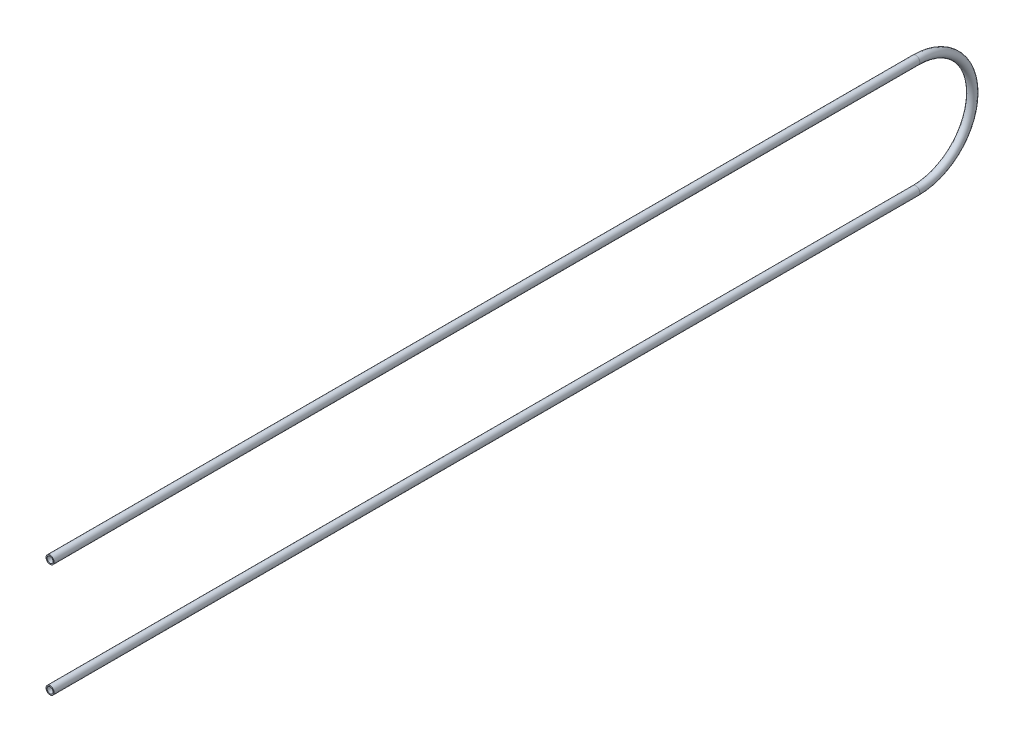
SolidWorks part; units mm, degrees
material "ASTM A312 TP316"
ref_plane "Front Plane" through (0, 0, 0) normal (0, 0, 1) x (1, 0, 0)
ref_plane "Top Plane" through (0, 0, 0) normal (0, 1, 0) x (1, 0, 0)
ref_plane "Right Plane" through (0, 0, 0) normal (1, 0, 0) x (0, 0, -1)
sketch "Sketch1" plane through (0, 0, 0) normal (1, 0, 0) x (0, 0, -1)
  line L0 (0, 0) -> (93.4526, 0) construction
  line L1 (0, 149.225) -> (2286, 149.225)
  line L2 (0, -149.225) -> (2286, -149.225)
  arc A0 (2286, -149.225) -> (2286, 149.225) centre (2286, 0) ccw
  dimension "D1" = 149.225
  dimension "D2" = 2286
sketch "Sketch2" plane through (0, 0, 0) normal (0, 0, 1) x (1, 0, 0)
  circle A0 centre (0, 149.225) radius 10.668
  circle A1 centre (0, 149.225) radius 7.8994
  dimension "D1" = 21.336
  dimension "D2" = 15.7988
sweep "Sweep1" add profiles "Sketch2" path "Sketch1"
